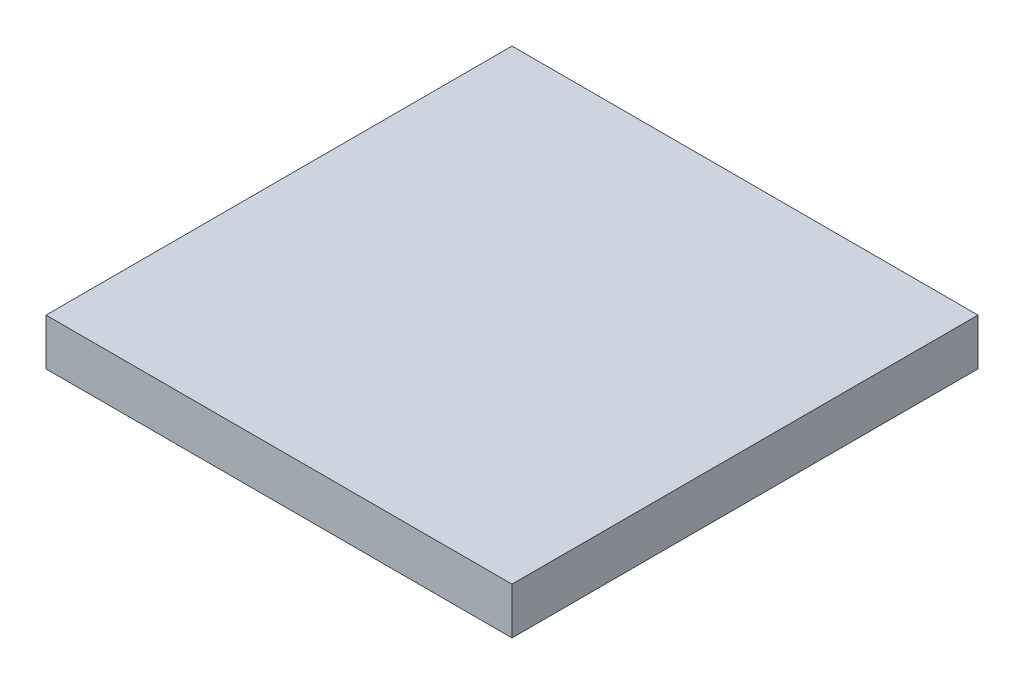
SolidWorks part; units mm, degrees
ref_plane "Front Plane" through (0, 0, 0) normal (0, 0, 1) x (1, 0, 0)
ref_plane "Top Plane" through (0, 0, 0) normal (0, 1, 0) x (1, 0, 0)
ref_plane "Right Plane" through (0, 0, 0) normal (1, 0, 0) x (0, 0, -1)
sketch "Sketch1" plane through (0, 0, 0) normal (0, 1, 0) x (1, 0, 0)
  line L1 (-250, 250) -> (250, 250)
  line L2 (-250, 250) -> (-250, -250)
  line L3 (-250, -250) -> (250, -250)
  line L4 (250, 250) -> (250, -250)
  line L5 (-250, 250) -> (250, -250) construction
  line L6 (-250, -250) -> (250, 250) construction
  point P0 (0, 0)
  dimension "D1" = 500
extrude "Boss-Extrude1" add sketch "Sketch1" along normal blind 50
